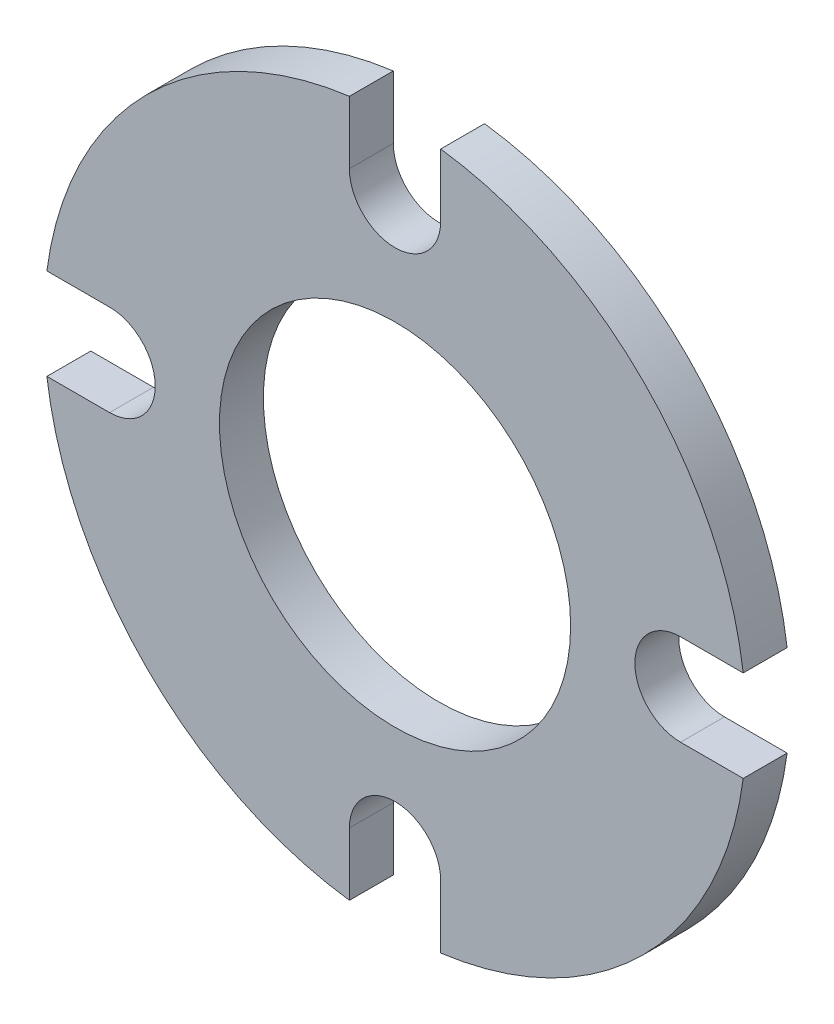
SolidWorks part; units mm, degrees
ref_plane "Front Plane" through (0, 0, 0) normal (0, 0, 1) x (1, 0, 0)
ref_plane "Top Plane" through (0, 0, 0) normal (0, 1, 0) x (1, 0, 0)
ref_plane "Right Plane" through (0, 0, 0) normal (1, 0, 0) x (0, 0, -1)
sketch "Sketch2" plane through (0, 0, 0) normal (0, 0, 1) x (1, 0, 0)
  line L0 (-0.13, 0.813) -> (-0.13, 0.9915)
  line L1 (0.13, 0.813) -> (0.13, 0.9915)
  line L2 (0.813, 0.13) -> (0.9915, 0.13)
  line L3 (0.813, -0.13) -> (0.9915, -0.13)
  line L4 (0.13, -0.813) -> (0.13, -0.9915)
  line L5 (-0.13, -0.813) -> (-0.13, -0.9915)
  line L6 (-0.813, -0.13) -> (-0.9915, -0.13)
  line L7 (-0.813, 0.13) -> (-0.9915, 0.13)
  circle A0 centre (0, 0) radius 0.5
  circle A1 centre (0, 0) radius 0.813 construction
  arc A2 (-0.13, 0.9915) -> (-0.9915, 0.13) centre (0, 0) ccw
  arc A3 (-0.13, 0.813) -> (0.13, 0.813) centre (0, 0.813) ccw
  circle A4 centre (0, 0) radius 0.5
  arc A5 (0.813, 0.13) -> (0.813, -0.13) centre (0.813, 0) ccw
  circle A6 centre (0, 0) radius 0.5
  arc A7 (0.13, -0.813) -> (-0.13, -0.813) centre (0, -0.813) ccw
  circle A8 centre (0, 0) radius 0.5
  arc A9 (-0.813, -0.13) -> (-0.813, 0.13) centre (-0.813, 0) ccw
  arc A10 (-0.9915, -0.13) -> (-0.13, -0.9915) centre (0, 0) ccw
  arc A11 (0.13, -0.9915) -> (0.9915, -0.13) centre (0, 0) ccw
  arc A12 (0.9915, 0.13) -> (0.13, 0.9915) centre (0, 0) ccw
  point P30 (0, 0)
  dimension "D1" = 1
  dimension "D2" = 2
  dimension "D3" = 1.626
  dimension "D4" = 0.26
  dimension "D5" = 4
extrude "Boss-Extrude1" add sketch "Sketch2" along normal blind 0.125 contours L2 A12 L1 A3 L0 A2 L7 A9 L6 A10 L5 A7 L4 A11 L3 A5 A0
